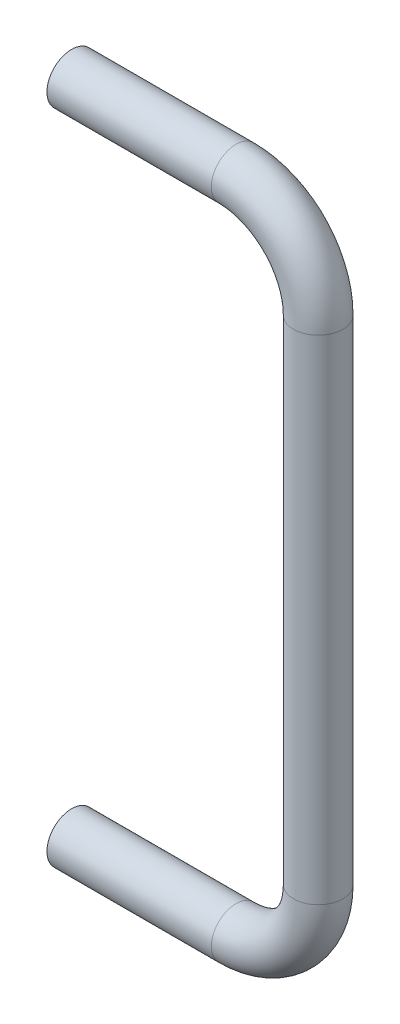
SolidWorks part; units mm, degrees
ref_plane "Ön Düzlem" through (0, 0, 0) normal (0, 0, 1) x (1, 0, 0)
ref_plane "Üst Düzlem" through (0, 0, 0) normal (0, 1, 0) x (1, 0, 0)
ref_plane "Sağ Düzlem" through (0, 0, 0) normal (1, 0, 0) x (0, 0, -1)
sketch "Çizim1" plane through (0, 0, 0) normal (0, 0, 1) x (1, 0, 0)
  line L0 (0, 0) -> (20, 0)
  line L1 (30, 10) -> (30, 70)
  line L2 (20, 80) -> (0, 80)
  arc A0 (20, 0) -> (30, 10) centre (20, 10) ccw
  arc A1 (30, 70) -> (20, 80) centre (20, 70) ccw
sketch "Çizim2" plane through (0, 0, 0) normal (1, 0, 0) x (0, 0, -1)
  circle A0 centre (0, 0) radius 3
sweep "Süpür1" add profiles "Çizim2" path "Çizim1"
